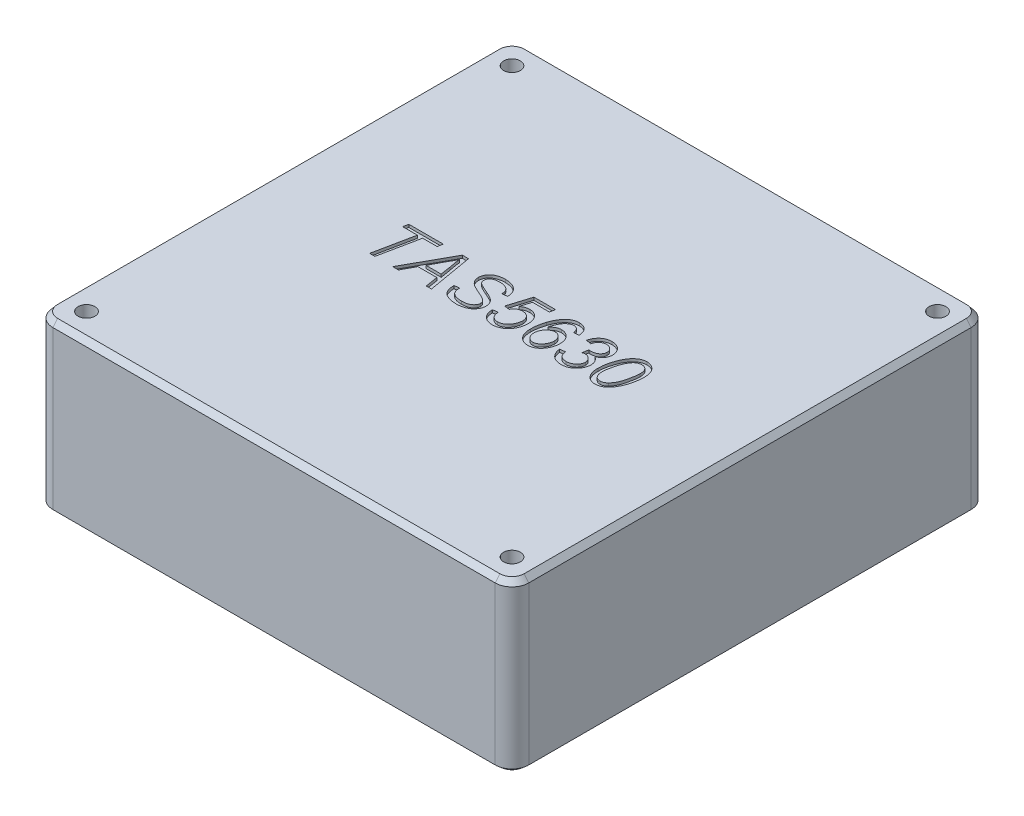
SolidWorks part; units mm, degrees
ref_plane "Спереди" through (0, 0, 0) normal (0, 0, 1) x (1, 0, 0)
ref_plane "Сверху" through (0, 0, 0) normal (0, 1, 0) x (1, 0, 0)
ref_plane "Справа" through (0, 0, 0) normal (1, 0, 0) x (0, 0, -1)
sketch "Эскиз1" plane through (0, 0, 0) normal (0, 1, 0) x (1, 0, 0)
  line L1 (-42.5, 42.5) -> (42.5, 42.5)
  line L2 (-42.5, 42.5) -> (-42.5, -42.5)
  line L3 (-42.5, -42.5) -> (42.5, -42.5)
  line L4 (42.5, 42.5) -> (42.5, -42.5)
  line L5 (-42.5, 42.5) -> (42.5, -42.5) construction
  line L6 (-42.5, -42.5) -> (42.5, 42.5) construction
  line L7 (38, -38) -> (-38, -38) construction
  line L8 (38, -38) -> (38, 38) construction
  line L9 (38, 38) -> (-38, 38) construction
  line L10 (-38, -38) -> (-38, 38) construction
  line L11 (38, -38) -> (-38, 38) construction
  line L12 (38, 38) -> (-38, -38) construction
  circle A0 centre (-38, 38) radius 1.5
  circle A1 centre (-38, -38) radius 1.5
  circle A2 centre (38, -38) radius 1.5
  circle A3 centre (38, 38) radius 1.5
  point P0 (0, 0)
  point P6 (0, 0)
  dimension "D1" = 3
  dimension "D2" = 76
  dimension "D3" = 85
extrude "Бобышка-Вытянуть1" add sketch "Эскиз1" along normal blind 30
sketch "Эскиз2" plane through (0, 0, 0) normal (0, 1, 0) x (1, 0, 0)
  text T0 "TAS5630" font "Arial" height 8
extrude "Вырез-Вытянуть1" cut sketch "Эскиз2" against normal blind 0.5 from surface at 30 starting at face at (38, 30, 39.5)
fillet "Скругление1" radius 3 4 edges at (-42.5, 15, -42.5) (42.5, 15, -42.5) (42.5, 15, 42.5) (-42.5, 15, 42.5)
chamfer "Фаска1" distance 1 angle 40 16 edges at (0, 0, -42.5) (-41.6213, 0, -41.6213) (41.6213, 0, -41.6213) (-42.5, 0, 0) (42.5, 0, 0) (-41.6213, 0, 41.6213) (41.6213, 0, 41.6213) (0, 0, 42.5) (0, 30, -42.5) (-41.6213, 30, -41.6213) (41.6213, 30, -41.6213) (-42.5, 30, 0) (42.5, 30, 0) (-41.6213, 30, 41.6213) (41.6213, 30, 41.6213) (0, 30, 42.5)
